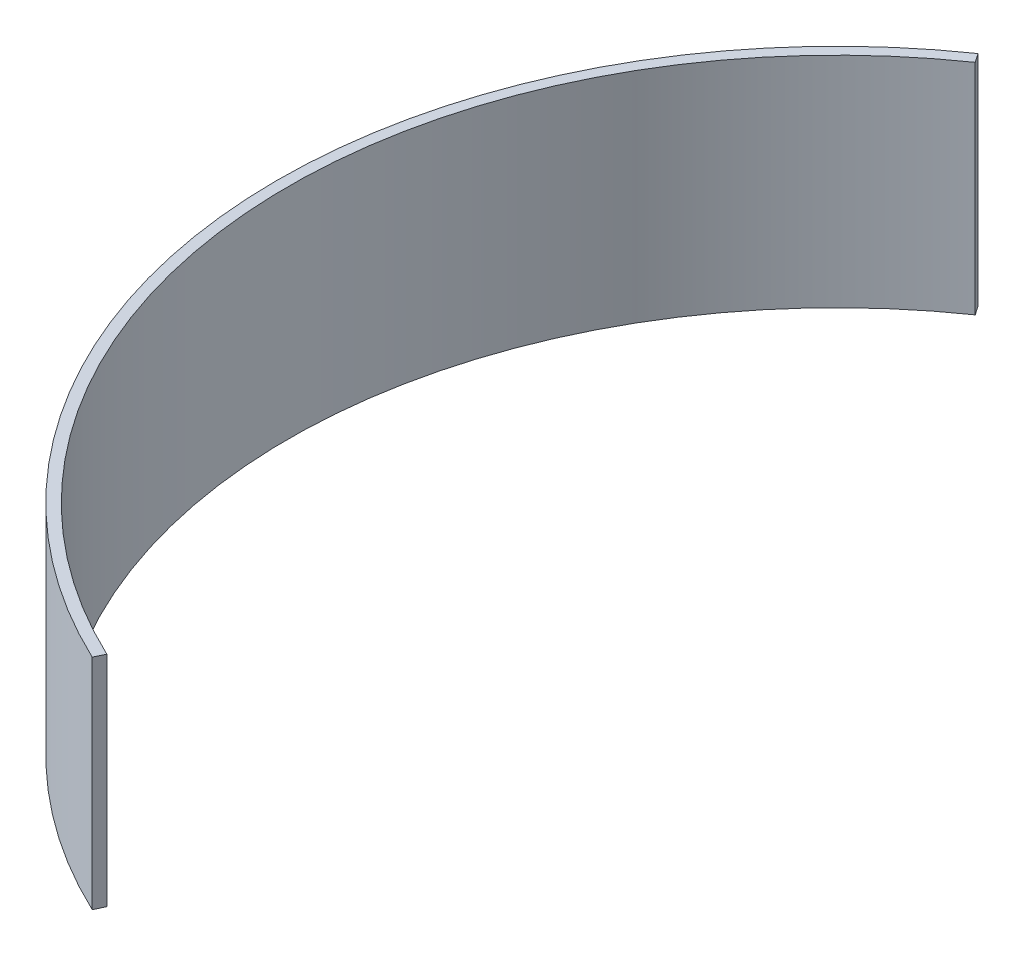
SolidWorks part; units mm, degrees
material "1060 Alloy"
ref_plane "Front Plane" through (0, 0, 0) normal (0, 0, 1) x (1, 0, 0)
ref_plane "Top Plane" through (0, 0, 0) normal (0, 1, 0) x (1, 0, 0)
ref_plane "Right Plane" through (0, 0, 0) normal (1, 0, 0) x (0, 0, -1)
sketch "Sketch2" plane through (0, 0, 0) normal (0, 1, 0) x (1, 0, 0)
  line L0 (-57.1413, 82.4377) -> (0, 0) construction
  line L1 (0, 0) -> (-42.8225, -90.7046) construction
  line L2 (-58.2806, 84.0814) -> (-57.1413, 82.4377)
  line L3 (-42.8225, -90.7046) -> (-43.6763, -92.5132)
  arc A0 (-42.8225, -90.7046) -> (-57.1413, 82.4377) centre (0, 0) cw
  arc A1 (-58.2806, 84.0814) -> (-43.6763, -92.5132) centre (0, 0) ccw
  dimension "D1" = 100.305
  dimension "D3" = 2
  dimension "D2" = 120
extrude "Boss-Extrude1" add sketch "Sketch2" along normal blind 40
